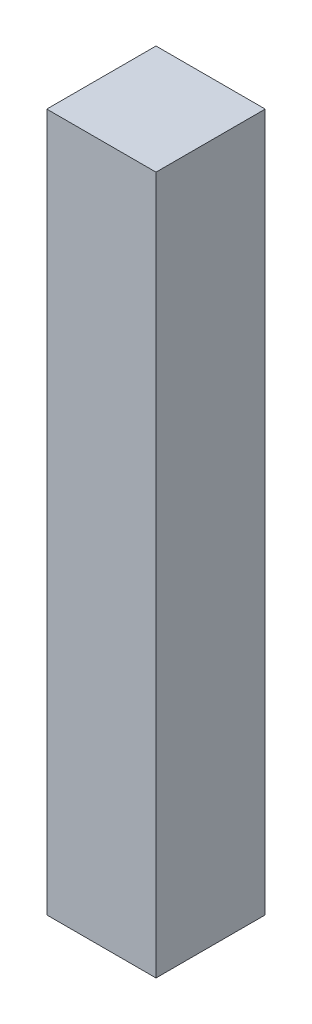
SolidWorks part; units mm, degrees
ref_plane "Front Plane" through (0, 0, 0) normal (0, 0, 1) x (1, 0, 0)
ref_plane "Top Plane" through (0, 0, 0) normal (0, 1, 0) x (1, 0, 0)
ref_plane "Right Plane" through (0, 0, 0) normal (1, 0, 0) x (0, 0, -1)
sketch "Sketch1" plane through (0, 0, 0) normal (0, 1, 0) x (1, 0, 0)
  line L1 (0, 0) -> (18, 0)
  line L2 (0, 0) -> (0, 18)
  line L3 (0, 18) -> (18, 18)
  line L4 (18, 0) -> (18, 18)
  dimension "D1" = 18
  dimension "D2" = 18
extrude "Boss-Extrude1" add sketch "Sketch1" along normal blind 115
